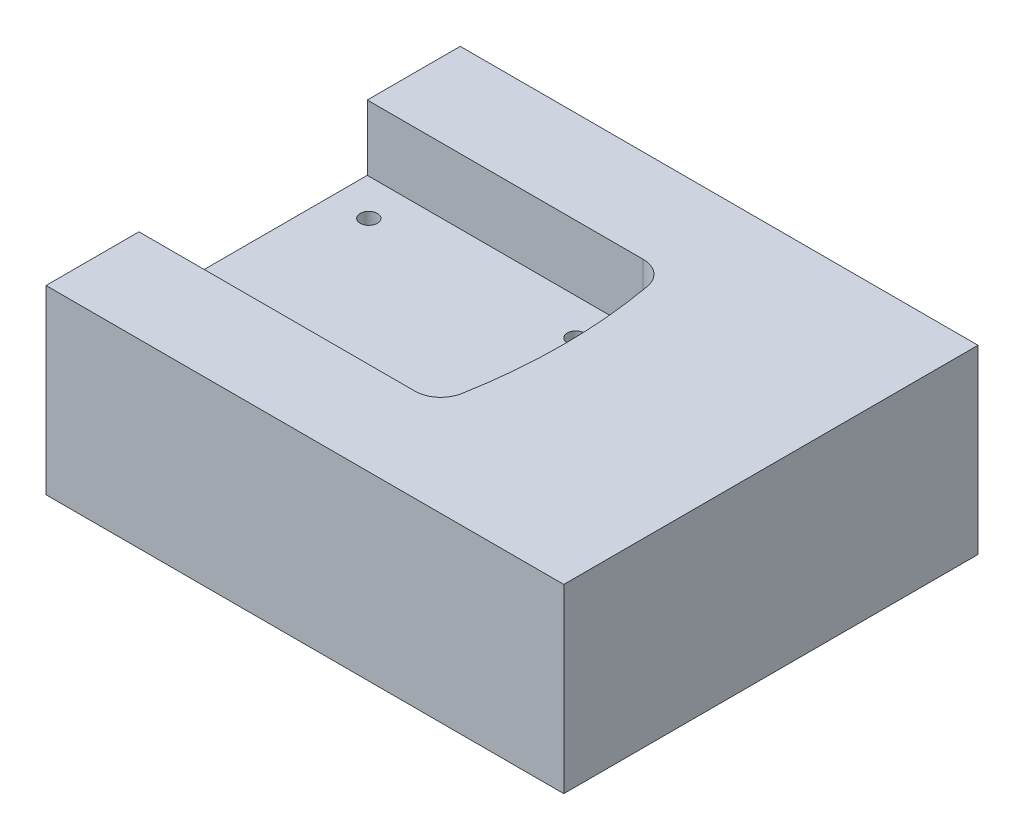
SolidWorks part; units mm, degrees
ref_plane "Front Plane" through (0, 0, 0) normal (0, 0, 1) x (1, 0, 0)
ref_plane "Top Plane" through (0, 0, 0) normal (0, 1, 0) x (1, 0, 0)
ref_plane "Right Plane" through (0, 0, 0) normal (1, 0, 0) x (0, 0, -1)
sketch "Sketch1" plane through (0, 0, 0) normal (0, 1, 0) x (1, 0, 0)
  line L1 (-63.5, 50.8) -> (63.5, 50.8)
  line L2 (-63.5, 50.8) -> (-63.5, -50.8)
  line L3 (-63.5, -50.8) -> (63.5, -50.8)
  line L4 (63.5, 50.8) -> (63.5, -50.8)
  line L5 (-63.5, 50.8) -> (63.5, -50.8) construction
  line L6 (-63.5, -50.8) -> (63.5, 50.8) construction
  point P0 (0, 0)
  dimension "D1" = 127
  dimension "D2" = 101.6
extrude "Boss-Extrude1" add sketch "Sketch1" along normal blind 44.45
sketch "Sketch2" plane through (0, 44.45, 0) normal (0, 1, 0) x (1, 0, 0)
  line L0 (-63.5, 50.8) -> (-63.5, -50.8) construction
  line L1 (-63.5, 28) -> (4.1916, 28)
  line L2 (-63.5, 28) -> (-63.5, -28)
  line L3 (-63.5, -28) -> (4.1916, -28)
  line L5 (9.3749, 28) -> (9.3749, -28) construction
  line L6 (0, 0) -> (-30.2069, 0) construction
  arc A0 (10.4385, 22.7895) -> (10.4385, -22.7895) centre (-114.5, 0) cw
  arc A1 (4.1916, -28) -> (10.4385, -22.7895) centre (4.1916, -21.65) ccw
  arc A2 (4.1916, 28) -> (10.4385, 22.7895) centre (4.1916, 21.65) cw
  point P7 (12.5, 0)
  dimension "D3" = 127
  dimension "D4" = 6.35
  dimension "D1" = 76
  dimension "D2" = 56
extrude "Cut-Extrude1" cut sketch "Sketch2" against normal blind 16
sketch "Sketch3" plane through (0, 28.45, 0) normal (0, 1, 0) x (1, 0, 0)
  line L0 (12.5, 0) -> (-23.2586, 0) construction
  line L1 (-54.175, 19.05) -> (-3.375, 19.05) construction
  line L2 (-54.175, 19.05) -> (-54.175, -19.05) construction
  line L3 (-54.175, -19.05) -> (-3.375, -19.05) construction
  line L4 (-3.375, 19.05) -> (-3.375, -19.05) construction
  circle A0 centre (-54.175, 19.05) radius 2.1082
  circle A1 centre (-54.175, -19.05) radius 2.1082
  circle A2 centre (-3.375, 19.05) radius 2.1082
  circle A3 centre (-3.375, -19.05) radius 2.1082
  arc A4 (10.4385, -22.7895) -> (10.4385, 22.7895) centre (-114.5, 0) ccw construction
  dimension "D1" = 4.2164
  dimension "D2" = 19.05
  dimension "D3" = 38.1
  dimension "D4" = 15.875
  dimension "D5" = 50.8
extrude "Cut-Extrude2" cut sketch "Sketch3" against normal through all
